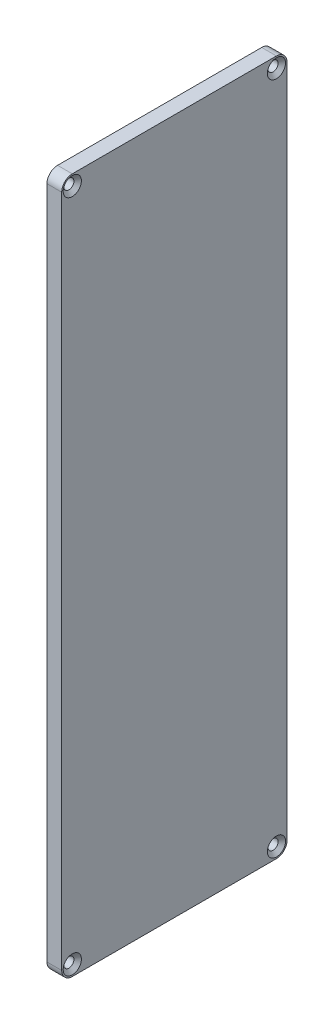
SolidWorks part; units mm, degrees
ref_plane "Front Plane" through (0, 0, 0) normal (1, 0, 0) x (0, 1, 0)
ref_plane "Top Plane" through (0, 0, 0) normal (0, 0, 1) x (0, 1, 0)
ref_plane "Right Plane" through (0, 0, 0) normal (0, 1, 0) x (-1, 0, 0)
sketch "Sketch1" plane through (0, 0, 0) normal (1, 0, 0) x (0, 1, 0)
  line L0 (-70.8025, 22.0654) -> (-70.8025, -19.5207)
  line L1 (-68.6435, -21.6797) -> (68.6435, -21.6797)
  line L2 (70.8025, -19.5207) -> (70.8025, 22.0654)
  line L3 (68.6435, 24.2244) -> (-68.6435, 24.2244)
  line L4 (-71.1835, 22.0654) -> (-71.1835, -19.5207)
  line L5 (-68.6435, -22.0607) -> (68.6435, -22.0607)
  line L6 (71.1835, -19.5207) -> (71.1835, 22.0654)
  line L7 (68.6435, 24.6054) -> (-68.6435, 24.6054)
  line L8 (-71.1835, 22.0654) -> (-71.1835, -19.5207) construction
  line L9 (-68.6435, -22.0607) -> (68.6435, -22.0607) construction
  line L10 (71.1835, -19.5207) -> (71.1835, 22.0654) construction
  line L11 (68.6435, 24.6054) -> (-68.6435, 24.6054) construction
  arc A0 (-70.8025, -19.5207) -> (-68.6435, -21.6797) centre (-68.6435, -19.5207) ccw
  arc A1 (68.6435, -21.6797) -> (70.8025, -19.5207) centre (68.6435, -19.5207) ccw
  arc A2 (70.8025, 22.0654) -> (68.6435, 24.2244) centre (68.6435, 22.0654) ccw
  arc A3 (-68.6435, 24.2244) -> (-70.8025, 22.0654) centre (-68.6435, 22.0654) ccw
  arc A4 (-71.1835, -19.5207) -> (-68.6435, -22.0607) centre (-68.6435, -19.5207) ccw
  arc A5 (68.6435, -22.0607) -> (71.1835, -19.5207) centre (68.6435, -19.5207) ccw
  arc A6 (71.1835, 22.0654) -> (68.6435, 24.6054) centre (68.6435, 22.0654) ccw
  arc A7 (-68.6435, 24.6054) -> (-71.1835, 22.0654) centre (-68.6435, 22.0654) ccw
  arc A8 (-71.1835, -19.5207) -> (-68.6435, -22.0607) centre (-68.6435, -19.5207) ccw construction
  arc A9 (68.6435, -22.0607) -> (71.1835, -19.5207) centre (68.6435, -19.5207) ccw construction
  arc A10 (71.1835, 22.0654) -> (68.6435, 24.6054) centre (68.6435, 22.0654) ccw construction
  arc A11 (-68.6435, 24.6054) -> (-71.1835, 22.0654) centre (-68.6435, 22.0654) ccw construction
  dimension "D1" = 0
  dimension "D2" = 0.381
extrude "Boss-Extrude1" add sketch "Sketch1" along normal up to surface (3 mm away)
hole_wizard "CSK for #1 Flat Head Machine Screw (100)1" positions "Sketch2" profile "Sketch3" countersink size "#1" standard "ANSI Inch" end condition through all
sketch "Sketch2" plane through (3, 0, 0) normal (1, 0, 0) x (0, 1, 0)
  arc A0 (-68.6435, 24.2244) -> (-70.8025, 22.0654) centre (-68.6435, 22.0654) ccw construction
  arc A1 (-70.8025, -19.5207) -> (-68.6435, -21.6797) centre (-68.6435, -19.5207) ccw construction
  arc A2 (68.6435, -21.6797) -> (70.8025, -19.5207) centre (68.6435, -19.5207) ccw construction
  arc A3 (70.8025, 22.0654) -> (68.6435, 24.2244) centre (68.6435, 22.0654) ccw construction
  point P0 (68.6435, 22.0654)
  point P2 (68.6435, -19.5207)
  point P4 (-68.6435, -19.5207)
  point P6 (-68.6435, 22.0654)
sketch "Sketch3" plane through (3, 68.6435, 22.0654) normal (0, 1, 0) x (0, 0, -1)
  line L0 (0, 0) -> (0, 3)
  line L1 (0, 3) -> (1.0287, 3)
  line L2 (1.0287, 3) -> (1.0287, 0.6927)
  line L3 (1.0287, 0.6927) -> (1.8542, 0)
  line L5 (1.8542, 0) -> (0, 0)
  line L6 (-1.0287, 0.6927) -> (-1.8542, 0) construction
  line L11 (0, -6.35) -> (0, 107.95) construction
  dimension "Thru Hole Dia." = 2.0574
  dimension "Thru Hole Depth" = 3
  dimension "Near C'Sink Dia." = 3.7084
  dimension "Near C'Sink Angle" = 100
